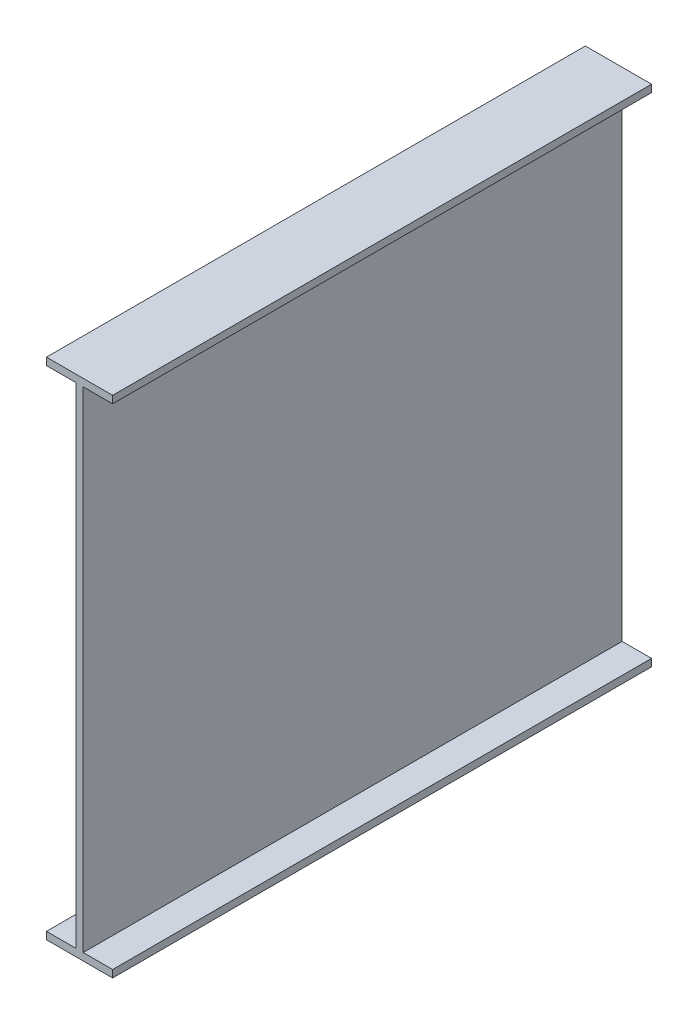
SolidWorks part; units mm, degrees
ref_plane "前视基准面" through (0, 0, 0) normal (0, 0, 1) x (1, 0, 0)
ref_plane "上视基准面" through (0, 0, 0) normal (0, 1, 0) x (1, 0, 0)
ref_plane "右视基准面" through (0, 0, 0) normal (1, 0, 0) x (0, 0, -1)
sketch "草图3" plane through (0, 0, 0) normal (0, 0, 1) x (1, 0, 0)
  line L2 (1.5, -100) -> (1.5, 100)
  line L4 (-1.5, -100) -> (-1.5, 100)
  line L5 (1.5, -100) -> (-1.5, 100) construction
  line L6 (1.5, 100) -> (-1.5, -100) construction
  line L7 (-1.5, 103) -> (13.5, 103)
  line L8 (13.5, 103) -> (13.5, 100)
  line L9 (13.5, 100) -> (1.5, 100)
  line L11 (-1.5, -103) -> (13.5, -103)
  line L12 (13.5, -103) -> (13.5, -100)
  line L13 (13.5, -100) -> (1.5, -100)
  line L14 (-1.5, 100) -> (-13.5, 100)
  line L15 (-13.5, 100) -> (-13.5, 103)
  line L16 (-13.5, 103) -> (-1.5, 103)
  line L17 (-1.5, -100) -> (-13.5, -100)
  line L18 (-13.5, -100) -> (-13.5, -103)
  line L19 (-13.5, -103) -> (-1.5, -103)
  point P0 (0, 0)
  dimension "D1" = 200
  dimension "D2" = 3
extrude "凸台-拉伸6" add sketch "草图3" along normal blind 220
